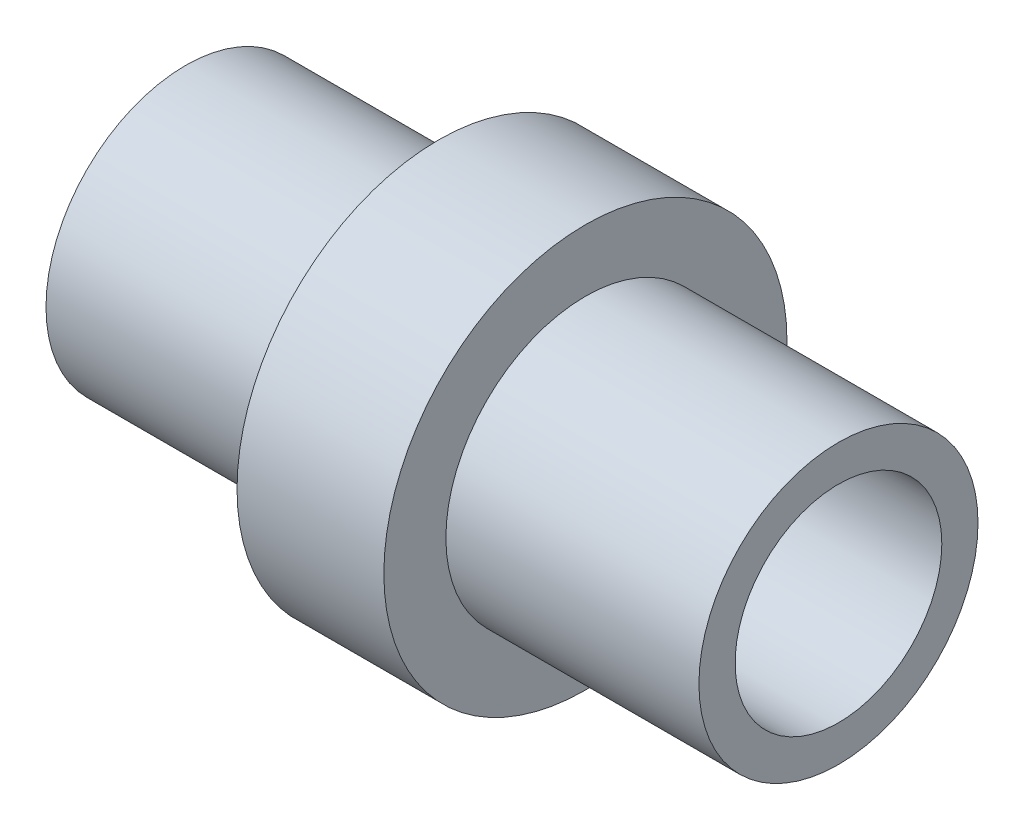
SolidWorks part; units mm, degrees
ref_plane "Front Plane" through (0, 0, 0) normal (0, 0, 1) x (1, 0, 0)
ref_plane "Top Plane" through (0, 0, 0) normal (0, 1, 0) x (1, 0, 0)
ref_plane "Right Plane" through (0, 0, 0) normal (1, 0, 0) x (0, 0, -1)
sketch "Sketch2" plane through (0, 0, 0) normal (0, 1, 0) x (1, 0, 0)
  line L0 (-20.0557, 8.5725) -> (-4.5102, 8.5725)
  line L1 (-4.5102, 8.5725) -> (-4.5102, 12.3825)
  line L2 (-4.5102, 12.3825) -> (4.5102, 12.3825)
  line L3 (4.5102, 12.3825) -> (4.5102, 8.5725)
  line L4 (4.5102, 8.5725) -> (20.0557, 8.5725)
  line L5 (20.0557, 8.5725) -> (20.0557, 0)
  line L6 (20.0557, 0) -> (-20.0557, 0)
  line L7 (-20.0557, 0) -> (-20.0557, 8.5725)
  point P5 (0, 0)
  point P10 (0, 12.3825)
  dimension "D1" = 8.5725
  dimension "D2" = 3.81
revolve "Revolve1" add sketch "Sketch2" angle 360 about L6
sketch "Sketch3" plane through (20.0557, 0, 0) normal (1, 0, 0) x (0, 0, -1)
  circle A0 centre (0, 0) radius 6.35
  dimension "D1" = 12.7
extrude "Cut-Extrude1" cut sketch "Sketch3" against normal through all both and the other way through all
